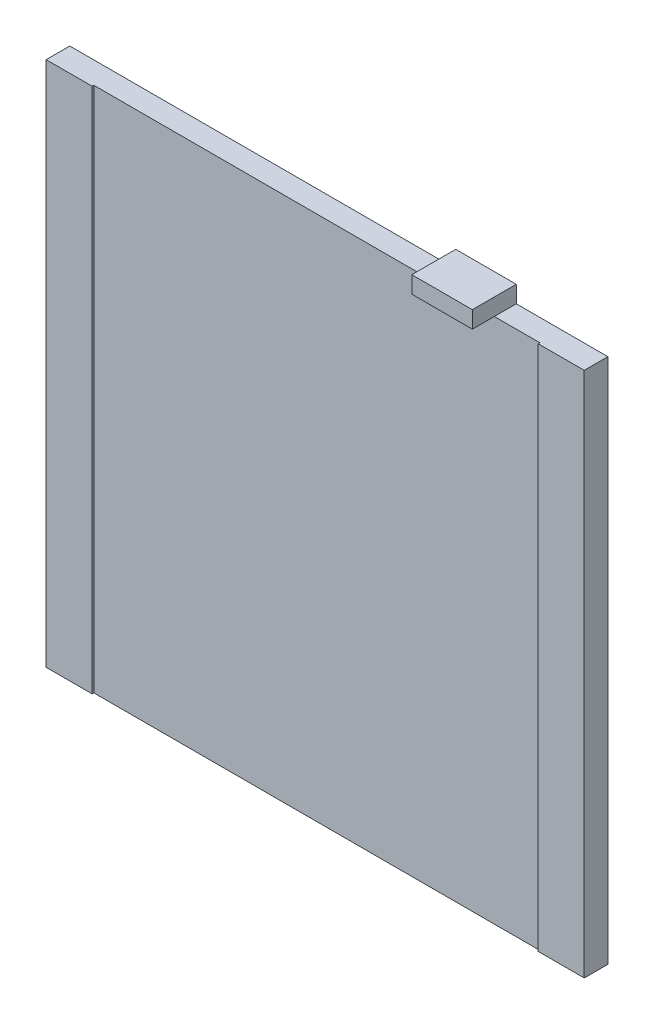
SolidWorks part; units mm, degrees
ref_plane "Front Plane" through (0, 0, 0) normal (0, 0, 1) x (1, 0, 0)
ref_plane "Top Plane" through (0, 0, 0) normal (0, 1, 0) x (1, 0, 0)
ref_plane "Right Plane" through (0, 0, 0) normal (1, 0, 0) x (0, 0, -1)
sketch "Sketch1" plane through (0, 0, 0) normal (0, 0, 1) x (1, 0, 0)
  line L1 (0, 0) -> (159.25, 0)
  line L2 (0, 0) -> (0, 155.74)
  line L3 (0, 155.74) -> (159.25, 155.74)
  line L4 (159.25, 0) -> (159.25, 155.74)
  dimension "D1" = 159.25
  dimension "D2" = 155.74
extrude "Boss-Extrude1" add sketch "Sketch1" along normal blind 6.5
sketch "Sketch2" plane through (0, 0, 6.5) normal (0, 0, 1) x (1, 0, 0)
  line L0 (0, 0) -> (159.25, 0) construction
  line L1 (0, 155.74) -> (13.61, 155.74)
  line L2 (0, 155.74) -> (0, 0)
  line L3 (0, 0) -> (13.61, 0)
  line L4 (13.61, 155.74) -> (13.61, 0)
  line L6 (159.25, 155.74) -> (145.64, 155.74)
  line L7 (159.25, 155.74) -> (159.25, 0)
  line L8 (159.25, 0) -> (145.64, 0)
  line L9 (145.64, 155.74) -> (145.64, 0)
  dimension "D1" = 13.61
extrude "Boss-Extrude2" add sketch "Sketch2" along normal blind 0.5 contours L9 L8 L7 L6 | L4 L3 L2 L1
sketch "Sketch3" plane through (0, 155.74, 0) normal (0, 1, 0) x (1, 0, 0)
  line L0 (159.25, 0) -> (0, 0) construction
  line L1 (132.14, 0) -> (114.22, 0)
  line L2 (132.14, 0) -> (132.14, -13)
  line L3 (132.14, -13) -> (114.22, -13)
  line L4 (114.22, 0) -> (114.22, -13)
  line L5 (159.25, -7) -> (159.25, 0) construction
  dimension "D1" = 17.92
  dimension "D2" = 13
  dimension "D3" = 27.11
extrude "Boss-Extrude3" add sketch "Sketch3" along normal blind 5
